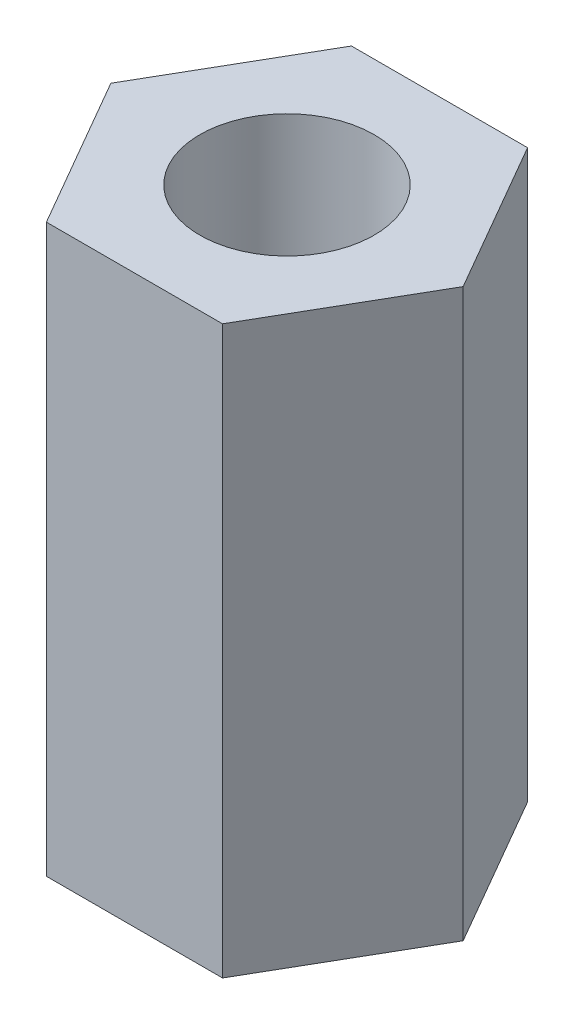
SolidWorks part; units mm, degrees
ref_plane "Front Plane" through (0, 0, 0) normal (0, 0, 1) x (1, 0, 0)
ref_plane "Top Plane" through (0, 0, 0) normal (0, 1, 0) x (1, 0, 0)
ref_plane "Right Plane" through (0, 0, 0) normal (1, 0, 0) x (0, 0, -1)
sketch "Sketch1" plane through (0, 0, 0) normal (0, 1, 0) x (1, 0, 0)
  line L1 (2.0207, 3.5) -> (-2.0207, 3.5)
  line L2 (-2.0207, 3.5) -> (-4.0415, 0)
  line L3 (-4.0415, 0) -> (-2.0207, -3.5)
  line L4 (-2.0207, -3.5) -> (2.0207, -3.5)
  line L5 (2.0207, -3.5) -> (4.0415, 0)
  line L6 (4.0415, 0) -> (2.0207, 3.5)
  circle A0 centre (0, 0) radius 3.5 construction
  circle A1 centre (0, 0) radius 2
  dimension "D1" = 7
  dimension "D2" = 4
extrude "Boss-Extrude1" add sketch "Sketch1" along normal blind 13
